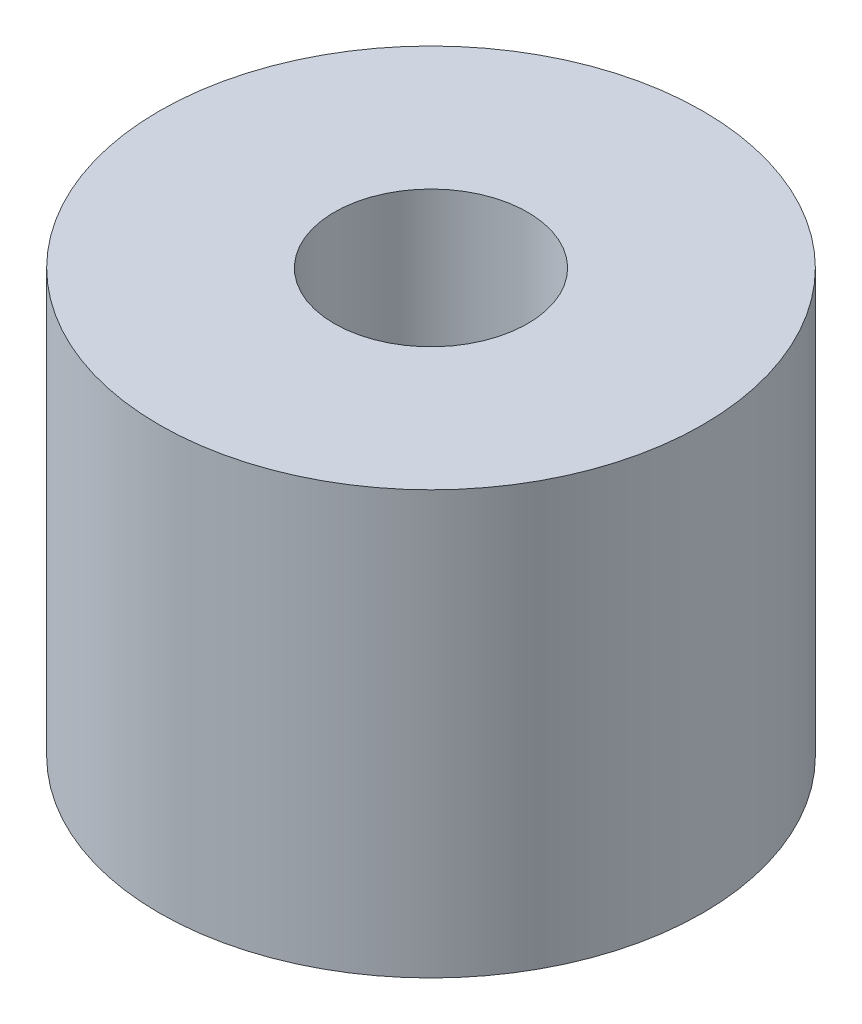
SolidWorks part; units mm, degrees
ref_plane "Front Plane" through (0, 0, 0) normal (0, 0, 1) x (1, 0, 0)
ref_plane "Top Plane" through (0, 0, 0) normal (0, 1, 0) x (1, 0, 0)
ref_plane "Right Plane" through (0, 0, 0) normal (1, 0, 0) x (0, 0, -1)
sketch "Sketch1" plane through (0, 0, 0) normal (0, 1, 0) x (1, 0, 0)
  circle A0 centre (0, 0) radius 1.6
  circle A1 centre (0, 0) radius 4.5
  dimension "D1" = 3.2
  dimension "D2" = 9
extrude "Boss-Extrude1" add sketch "Sketch1" along normal blind 7
